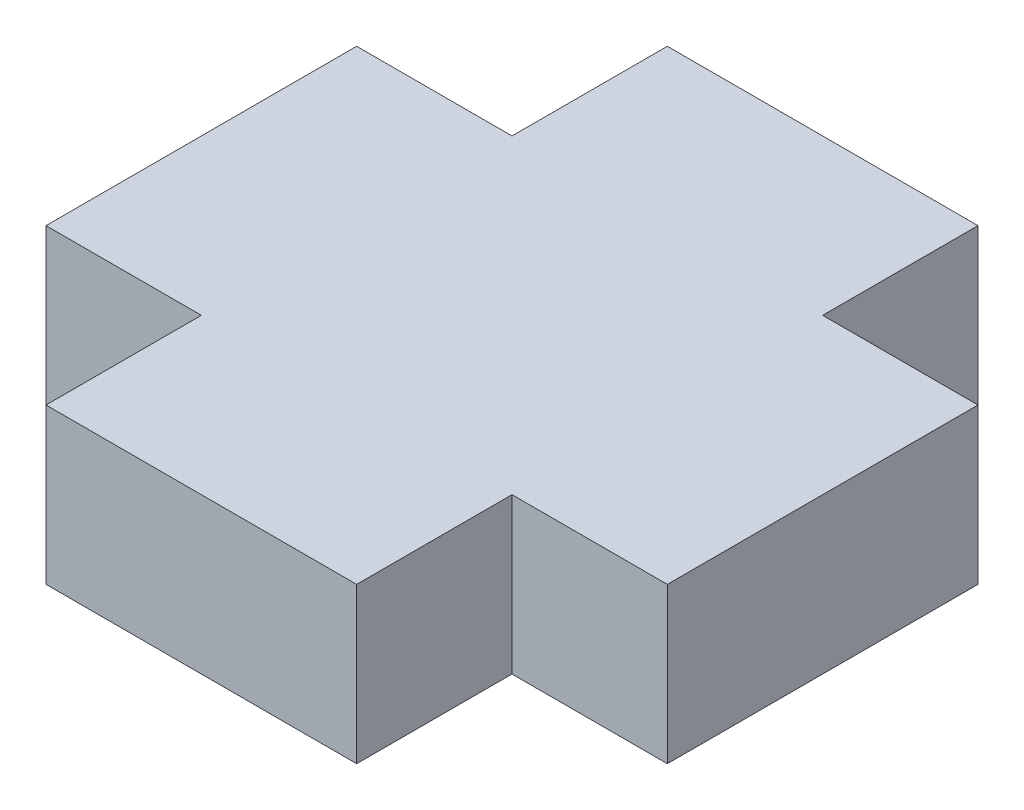
SolidWorks part; units mm, degrees
ref_plane "前视基准面" through (0, 0, 0) normal (0, 0, 1) x (1, 0, 0)
ref_plane "上视基准面" through (0, 0, 0) normal (0, 1, 0) x (1, 0, 0)
ref_plane "右视基准面" through (0, 0, 0) normal (1, 0, 0) x (0, 0, -1)
sketch "草图1" plane through (0, 0, 0) normal (0, 1, 0) x (1, 0, 0)
  line L0 (15, 10) -> (20, 10)
  line L1 (0, 0) -> (5, 0)
  line L2 (0, 0) -> (0, 10)
  line L3 (0, 10) -> (5, 10)
  line L4 (20, 0) -> (20, 10)
  line L6 (5, 10) -> (5, 15)
  line L7 (5, 15) -> (15, 15)
  line L8 (15, 10) -> (15, 15)
  line L10 (5, 0) -> (5, -5)
  line L11 (5, -5) -> (15, -5)
  line L12 (15, 0) -> (15, -5)
  line L13 (15, 0) -> (20, 0)
  dimension "D1" = 20
  dimension "D2" = 10
  dimension "D3" = 10
  dimension "D4" = 10
  dimension "D5" = 5
  dimension "D6" = 5
  dimension "D7" = 5
  dimension "D8" = 5
extrude "凸台-拉伸1" add sketch "草图1" along normal blind 5
